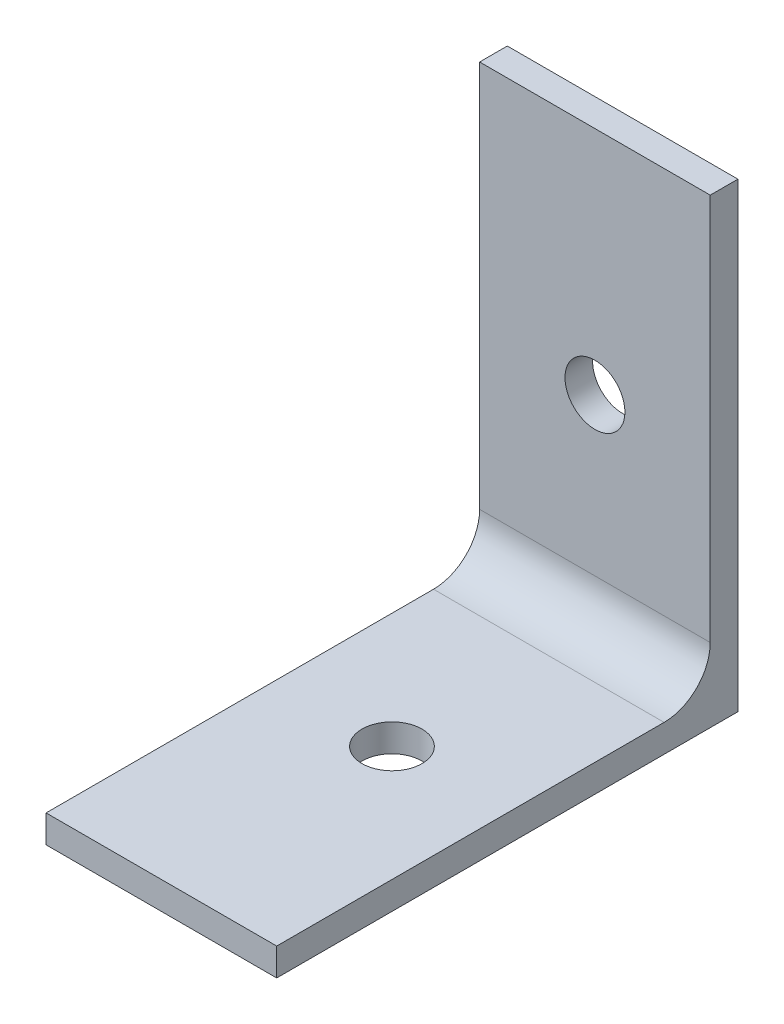
SolidWorks part; units mm, degrees
ref_plane "Front Plane" through (0, 0, 0) normal (0, 0, 1) x (1, 0, 0)
ref_plane "Top Plane" through (0, 0, 0) normal (0, 1, 0) x (1, 0, 0)
ref_plane "Right Plane" through (0, 0, 0) normal (1, 0, 0) x (0, 0, -1)
sketch "Sketch2" plane through (0, 0, 0) normal (0, 0, 1) x (1, 0, 0)
  line L1 (-18.534, 23.876) -> (-5.834, 23.876)
  line L2 (-18.534, 23.876) -> (-18.534, 0)
  line L3 (-18.534, 0) -> (-5.834, 0)
  line L4 (-5.834, 23.876) -> (-5.834, 0)
  dimension "D1" = 23.876
  dimension "D2" = 12.7
  dimension "D3" = 5.834
extrude "Boss-Extrude1" add sketch "Sketch2" along normal blind 1.524
sketch "Sketch3" plane through (0, 0, 0) normal (0, -1, 0) x (1, 0, 0)
  line L0 (-5.834, 1.524) -> (-5.834, 0) construction
  line L1 (-18.534, 0) -> (-5.834, 0)
  line L2 (-18.534, 0) -> (-18.534, 25.4)
  line L3 (-18.534, 25.4) -> (-5.834, 25.4)
  line L4 (-5.834, 0) -> (-5.834, 25.4)
extrude "Boss-Extrude2" add sketch "Sketch3" along normal blind 1.524
fillet "Fillet1" radius 2.54 1 edges
sketch "Sketch4" plane through (0, 0, 1.524) normal (0, 0, 1) x (1, 0, 0)
  line L0 (-5.834, 23.876) -> (-18.534, 23.876) construction
  line L1 (-5.834, 2.54) -> (-5.834, 23.876) construction
  circle A0 centre (-12.184, 11.176) radius 1.651
  dimension "D3" = 3.302
  dimension "D1" = 12.7
  dimension "D2" = 6.35
extrude "Cut-Extrude1" cut sketch "Sketch4" against normal through all
sketch "Sketch5" plane through (0, 0, 0) normal (0, 1, 0) x (1, 0, 0)
  line L0 (-5.834, -4.064) -> (-5.834, -25.4) construction
  line L1 (-5.834, -25.4) -> (-18.534, -25.4) construction
  circle A0 centre (-12.184, -12.7) radius 1.651
  dimension "D1" = 6.35
  dimension "D2" = 12.7
  dimension "D3" = 3.302
extrude "Cut-Extrude2" cut sketch "Sketch5" against normal blind 1.524
